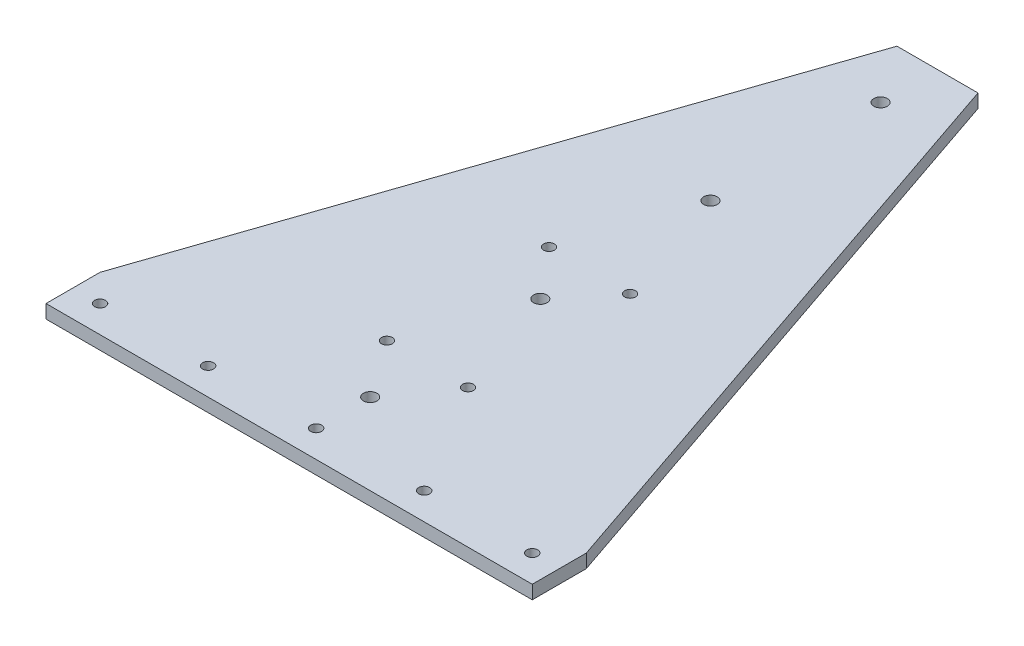
SolidWorks part; units mm, degrees
ref_plane "Front Plane" through (0, 0, 0) normal (0, 0, 1) x (1, 0, 0)
ref_plane "Top Plane" through (0, 0, 0) normal (0, 1, 0) x (1, 0, 0)
ref_plane "Right Plane" through (0, 0, 0) normal (1, 0, 0) x (0, 0, -1)
sketch "Sketch1" plane through (0, 0, 0) normal (0, 1, 0) x (1, 0, 0)
  line L1 (0, 0) -> (228.6, 0)
  line L2 (0, 0) -> (0, 25.4)
  line L4 (228.6, 0) -> (228.6, 25.4)
  line L5 (95.25, 304.8) -> (0, 25.4)
  line L7 (95.25, 304.8) -> (133.35, 304.8)
  line L9 (133.35, 304.8) -> (228.6, 25.4)
  point P9 (114.3, 304.8)
  point P10 (114.3, 0)
  dimension "D1" = 228.6
  dimension "D2" = 25.4
  dimension "D3" = 304.8
  dimension "D4" = 38.1
extrude "Boss-Extrude1" add sketch "Sketch1" along normal blind 6.35
sketch "Sketch2" plane through (0, 6.35, 0) normal (0, 1, 0) x (1, 0, 0)
  line L0 (0, 12.7) -> (228.6, 12.7) construction
  line L1 (0, 25.4) -> (0, 0) construction
  line L2 (228.6, 0) -> (228.6, 25.4) construction
  line L4 (114.3, 304.8) -> (114.3, 0) construction
  line L5 (133.35, 304.8) -> (95.25, 304.8) construction
  line L6 (0, 0) -> (228.6, 0) construction
  circle A0 centre (165.1, 12.7) radius 2.5797
  circle A1 centre (114.3, 12.7) radius 2.5797
  circle A2 centre (63.5, 12.7) radius 2.5797
  circle A3 centre (114.3, 38.1) radius 3.175
  circle A4 centre (114.3, 118.0846) radius 3.175
  circle A5 centre (114.3, 198.0692) radius 3.175
  circle A6 centre (114.3, 278.0538) radius 3.175
  circle A7 centre (12.7, 12.7) radius 2.5797
  circle A8 centre (215.9, 12.7) radius 2.5797
  dimension "D1" = 50.8
  dimension "D2" = 50.8
  dimension "D3" = 5.1594
  dimension "D4" = 6.35
  dimension "D6" = 79.9846
  dimension "D7" = 79.9846
  dimension "D8" = 79.9846
  dimension "D9" = 50.8
  dimension "D10" = 50.8
  dimension "D5" = 38.1
extrude "Cut-Extrude1" cut sketch "Sketch2" against normal through all
sketch "Sketch3" plane through (0, 6.35, 0) normal (0, 1, 0) x (1, 0, 0)
  line L0 (114.3, 0) -> (114.3, 304.8) construction
  line L1 (0, 0) -> (228.6, 0) construction
  line L2 (133.35, 304.8) -> (95.25, 304.8) construction
  line L3 (133.35, 141.224) -> (95.25, 141.224) construction
  line L4 (133.35, 65.024) -> (95.25, 65.024) construction
  circle A0 centre (133.35, 65.024) radius 1.905
  circle A1 centre (95.25, 65.024) radius 1.905
  circle A2 centre (133.35, 141.224) radius 1.905
  circle A3 centre (95.25, 141.224) radius 1.905
  point P14 (114.3, 141.224)
  point P16 (114.3, 65.024)
  dimension "D1" = 3.81
  dimension "D2" = 76.2
  dimension "D3" = 38.1
  dimension "D5" = 38.1
  dimension "D6" = 65.024
extrude "Cut-Extrude2" cut sketch "Sketch3" against normal through all
hole_wizard "1/4-20 Tapped Hole1" positions "Sketch5" profile "Sketch6" tap size "1/4-20" standard "ANSI Inch"
sketch "Sketch5" plane through (0, 6.35, 0) normal (0, 1, 0) x (1, 0, 0)
  point P0 (95.25, 141.224)
  point P2 (133.35, 141.224)
  point P4 (133.35, 65.024)
  point P6 (95.25, 65.024)
sketch "Sketch6" plane through (95.25, 6.35, -141.224) normal (1, 0, 0) x (0, 0, 1)
  line L0 (0, 0) -> (0, 18.0438)
  line L1 (0, 18.0438) -> (2.5527, 16.51)
  line L2 (2.5527, 16.51) -> (2.5527, 0)
  line L5 (2.5527, 0) -> (0, 0)
  line L10 (0, 18.0438) -> (-2.5527, 16.51) construction
  line L11 (0, -6.35) -> (0, 107.95) construction
  dimension "Tap Drill Dia." = 5.1054
  dimension "Tap Drill Depth" = 16.51
  dimension "Drill Angle" = 118
cosmetic thread "Hole Thread1" parameters "D1"=6.35, "D2"=6.35
cosmetic thread "Hole Thread2" parameters "D1"=6.35, "D2"=6.35
cosmetic thread "Hole Thread3" parameters "D1"=6.35, "D2"=6.35
cosmetic thread "Hole Thread4" parameters "D1"=6.35, "D2"=6.35
